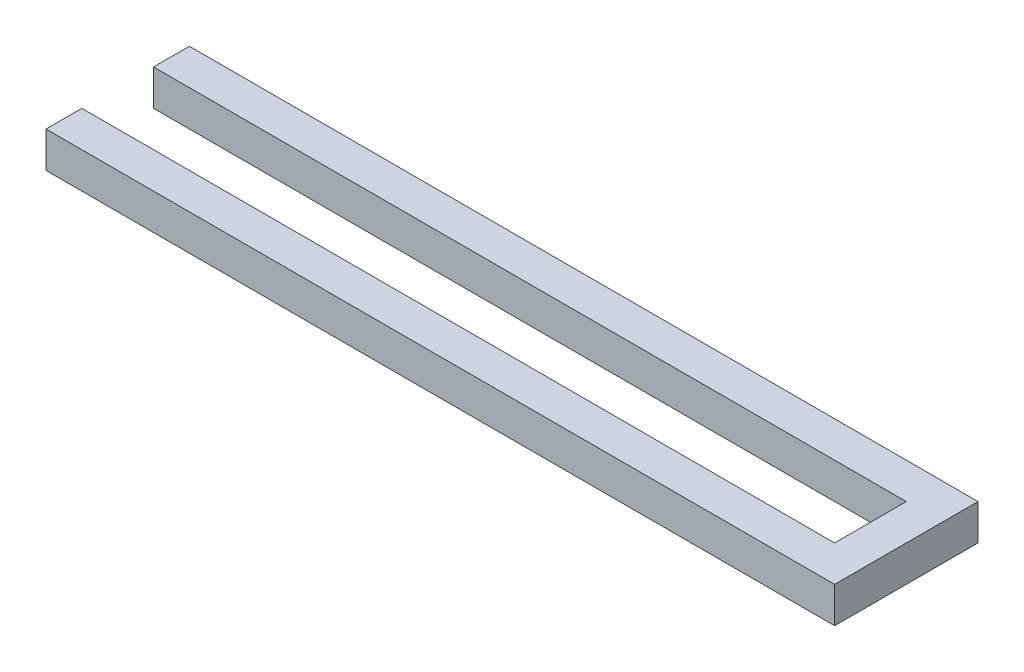
SolidWorks part; units mm, degrees
ref_plane "Front Plane" through (0, 0, 0) normal (0, 0, 1) x (1, 0, 0)
ref_plane "Top Plane" through (0, 0, 0) normal (0, 1, 0) x (1, 0, 0)
ref_plane "Right Plane" through (0, 0, 0) normal (1, 0, 0) x (0, 0, -1)
sketch "Sketch1" plane through (0, 0, 0) normal (0, 1, 0) x (1, 0, 0)
  line L1 (-27.0019, 20.9846) -> (182.9981, 20.9846)
  line L2 (-27.0019, 20.9846) -> (-27.0019, 10.9846)
  line L3 (-27.0019, 10.9846) -> (182.9981, 10.9846)
  line L4 (182.9981, 20.9846) -> (182.9981, 10.9846)
  line L5 (-27.0019, -9.0154) -> (182.9981, -9.0154)
  line L6 (-27.0019, -9.0154) -> (-27.0019, -19.0154)
  line L7 (-27.0019, -19.0154) -> (182.9981, -19.0154)
  line L8 (182.9981, -9.0154) -> (182.9981, -19.0154)
  line L9 (182.9981, 20.9846) -> (192.9981, 20.9846)
  line L10 (182.9981, 20.9846) -> (182.9981, -19.0154)
  line L11 (182.9981, -19.0154) -> (192.9981, -19.0154)
  line L12 (192.9981, 20.9846) -> (192.9981, -19.0154)
  dimension "D1" = 210
  dimension "D2" = 10
  dimension "D3" = 10
  dimension "D4" = 20
  dimension "D5" = 10
extrude "Boss-Extrude1" add sketch "Sketch1" along normal blind 10 contours L8 L5 L6 L7 | L12 L9 L4 L10 L8 L11 | L4 L1 L2 L3
